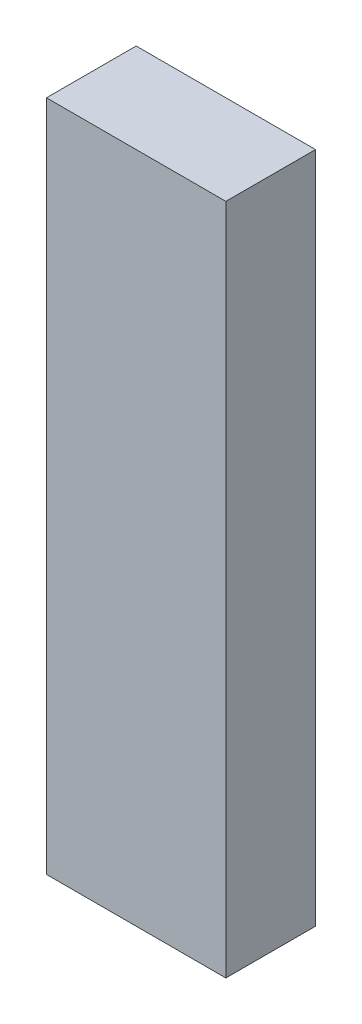
SolidWorks part; units mm, degrees
ref_plane "Front Plane" through (0, 0, 0) normal (0, 0, 1) x (1, 0, 0)
ref_plane "Top Plane" through (0, 0, 0) normal (0, 1, 0) x (1, 0, 0)
ref_plane "Right Plane" through (0, 0, 0) normal (1, 0, 0) x (0, 0, -1)
sketch "Sketch1" plane through (0, 0, 0) normal (0, 1, 0) x (1, 0, 0)
  line L1 (0, 0) -> (25.4, 0)
  line L2 (0, 0) -> (0, 12.7)
  line L3 (0, 12.7) -> (25.4, 12.7)
  line L4 (25.4, 0) -> (25.4, 12.7)
  dimension "D1" = 25.4
  dimension "D2" = 12.7
extrude "Boss-Extrude1" add sketch "Sketch1" along normal blind 95.25
sketch "Sketch2" plane through (0, 0, 0) normal (0, -1, 0) x (1, 0, 0)
  line L0 (0, -12.7) -> (0, 0) construction
  circle A0 centre (6.35, -6.35) radius 3.175
  circle A1 centre (19.05, -6.35) radius 3.175
  point P6 (0, -6.35)
  dimension "D1" = 6.35
  dimension "D2" = 6.35
  dimension "D3" = 12.7
extrude "Cut-Extrude1" cut sketch "Sketch2" against normal blind 25.4
